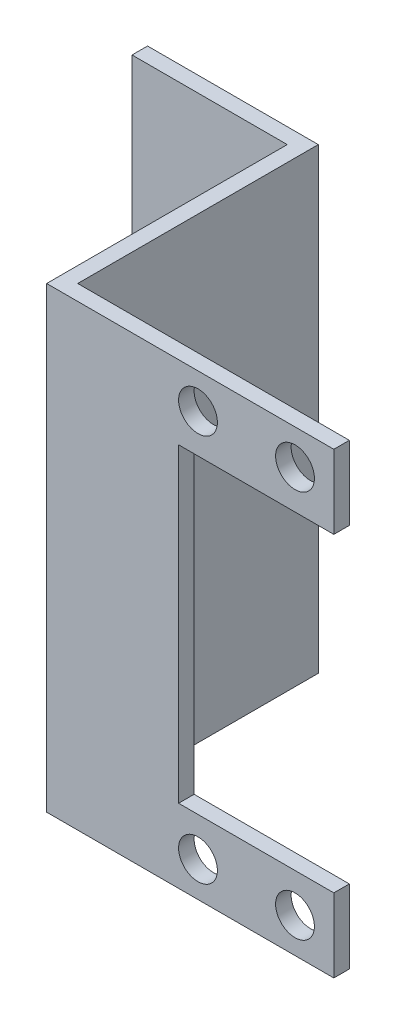
SolidWorks part; units mm, degrees
ref_plane "前视基准面" through (0, 0, 0) normal (0, 0, 1) x (1, 0, 0)
ref_plane "上视基准面" through (0, 0, 0) normal (0, 1, 0) x (1, 0, 0)
ref_plane "右视基准面" through (0, 0, 0) normal (1, 0, 0) x (0, 0, -1)
other "Configuration Table"
sketch "草图1" plane through (0, 0, 0) normal (0, 0, 1) x (1, 0, 0)
  line L0 (0, 0) -> (0, 59)
  line L1 (0, 59) -> (37, 59)
  line L2 (37, 59) -> (37, 0)
  line L3 (37, 0) -> (0, 0)
  dimension "D1" = 37
  dimension "D2" = 59
extrude "凸台-拉伸1" add sketch "草图1" along normal blind 2
sketch "草图2" plane through (0, 0, 2) normal (0, 0, 1) x (1, 0, 0)
  line L0 (37, 29.5) -> (-10.8284, 29.5) construction
  line L1 (37, 0) -> (37, 59) construction
  line L2 (37, 49.5) -> (17, 49.5)
  line L3 (17, 49.5) -> (17, 9.5)
  line L4 (17, 9.5) -> (37, 9.5)
  line L5 (37, 9.5) -> (37, 49.5)
  line L6 (37, 59) -> (0, 59) construction
  dimension "D1" = 40
  dimension "D2" = 20
  dimension "D3" = 9.5
extrude "切除-拉伸1" cut sketch "草图2" against normal blind 2
sketch "草图3" plane through (0, 0, 0) normal (0, 0, -1) x (-1, 0, 0)
  line L0 (0, 0) -> (-37, 0) construction
  line L1 (0, 59) -> (-2, 59)
  line L2 (0, 59) -> (0, 0)
  line L3 (0, 0) -> (-2, 0)
  line L4 (-2, 59) -> (-2, 0)
  dimension "D1" = 2
extrude "凸台-拉伸2" add sketch "草图3" along normal blind 31
sketch "草图4" plane through (0, 0, 0) normal (-1, 0, 0) x (0, 0, 1)
  line L0 (2, 0) -> (-31, 0) construction
  line L1 (-31, 59) -> (-29, 59)
  line L2 (-31, 59) -> (-31, 0)
  line L3 (-31, 0) -> (-29, 0)
  line L4 (-29, 59) -> (-29, 0)
  dimension "D1" = 2
extrude "凸台-拉伸3" add sketch "草图4" along normal blind 20
sketch "草图5" plane through (0, 0, -31) normal (0, 0, -1) x (-1, 0, 0)
  line L0 (20, 29.5) -> (-54.6766, 29.5) construction
  line L1 (20, 59) -> (20, 0) construction
  circle A0 centre (10, 44.5) radius 2
  circle A1 centre (10, 14.5) radius 2
  dimension "D1" = 4
  dimension "D2" = 30
  dimension "D3" = 10
extrude "切除-拉伸2" cut sketch "草图5" against normal blind 20
sketch "草图6" plane through (0, 0, 0) normal (0, 0, -1) x (-1, 0, 0)
  line L0 (-37, 59) -> (-2, 59) construction
  line L2 (-37, 49.5) -> (-37, 59) construction
  line L3 (-17, 29.5) -> (-45.0328, 29.5) construction
  line L4 (-17, 49.5) -> (-17, 9.5) construction
  circle A0 centre (-32, 54.5) radius 2.5
  circle A1 centre (-19.5, 54.5) radius 2.5
  circle A2 centre (-19.5, 4.5) radius 2.5
  circle A3 centre (-32, 4.5) radius 2.5
  dimension "D1" = 5
  dimension "D2" = 10
  dimension "D3" = 5
  dimension "D4" = 4.5
extrude "切除-拉伸3" cut sketch "草图6" against normal blind 20
